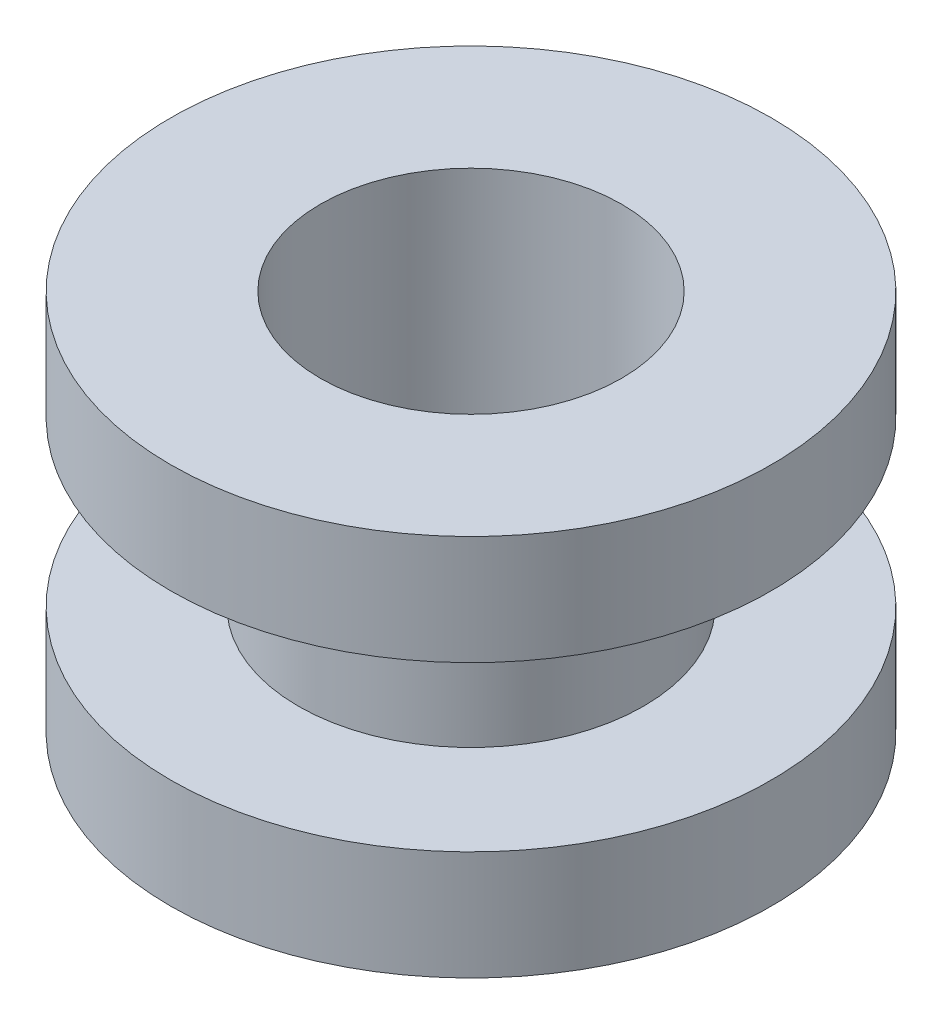
SolidWorks part; units mm, degrees
ref_plane "Front Plane" through (0, 0, 0) normal (0, 0, 1) x (1, 0, 0)
ref_plane "Top Plane" through (0, 0, 0) normal (0, 1, 0) x (1, 0, 0)
ref_plane "Right Plane" through (0, 0, 0) normal (1, 0, 0) x (0, 0, -1)
sketch "Sketch1" plane through (0, 0, 0) normal (0, 1, 0) x (1, 0, 0)
  circle A0 centre (0, 0) radius 17.526
  circle A1 centre (0, 0) radius 20.066
  dimension "D1" = 35.052
  dimension "D2" = 2.54
extrude "Extrude1" add sketch "Sketch1" along normal blind 44.45
sketch "Sketch2" plane through (0, 44.45, 0) normal (0, 1, 0) x (1, 0, 0)
  circle A0 centre (0, 0) radius 17.526
  circle A1 centre (0, 0) radius 34.925
  dimension "D1" = 69.85
extrude "Extrude2" add sketch "Sketch2" against normal blind 12.7
sketch "Sketch3" plane through (0, 0, 0) normal (0, -1, 0) x (1, 0, 0)
  circle A0 centre (0, 0) radius 17.526
  circle A1 centre (0, 0) radius 34.925
extrude "Extrude3" add sketch "Sketch3" against normal blind 12.7
